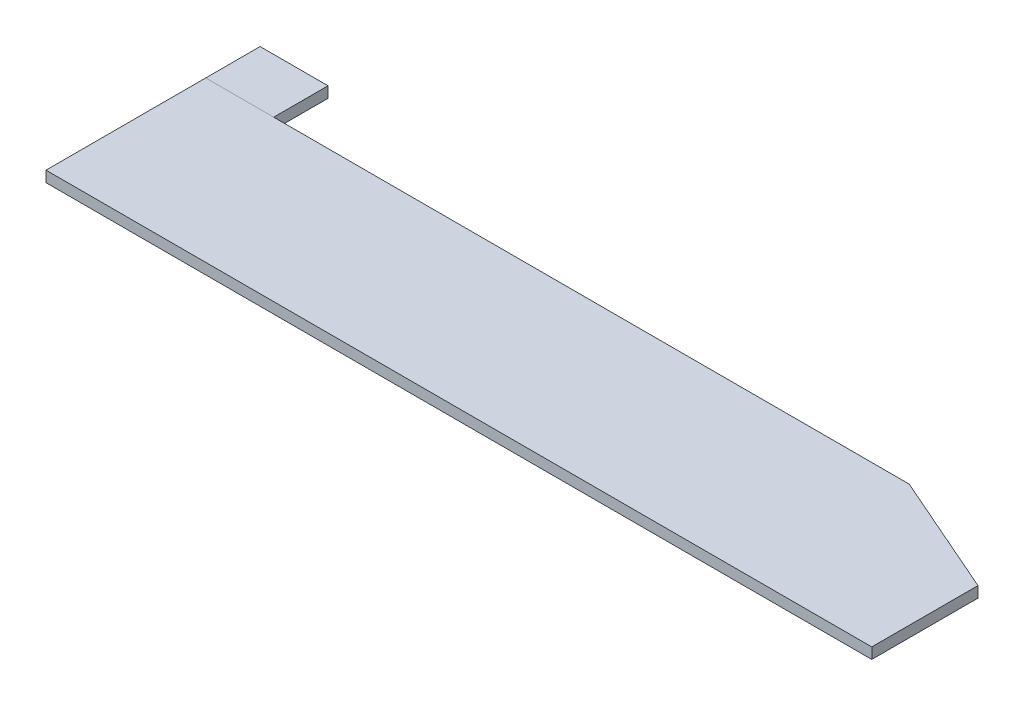
SolidWorks part; units mm, degrees
ref_plane "Front Plane" through (0, 0, 0) normal (0, 0, 1) x (1, 0, 0)
ref_plane "Top Plane" through (0, 0, 0) normal (0, 1, 0) x (1, 0, 0)
ref_plane "Right Plane" through (0, 0, 0) normal (1, 0, 0) x (0, 0, -1)
sketch "Sketch1" plane through (0, 0, 0) normal (0, 1, 0) x (1, 0, 0)
  line L0 (-43.4424, 9.168) -> (-43.4424, -14.332)
  line L1 (-43.4424, -14.332) -> (78.0576, -14.332)
  line L2 (78.0576, -14.332) -> (78.0576, 1.298)
  line L4 (60.0576, 9.168) -> (-43.4424, 9.168)
  line L5 (60.0576, 9.168) -> (78.0576, 1.298)
  dimension "D1" = 121.5
  dimension "D2" = 23.5
  dimension "D3" = 15.63
  dimension "D4" = 103.5
extrude "Boss-Extrude1" add sketch "Sketch1" along normal blind 1.6
sketch "Sketch2" plane through (0, 1.6, 0) normal (0, 1, 0) x (1, 0, 0)
  line L0 (-43.4424, -14.332) -> (78.0576, -14.332) construction
  line L1 (-43.4424, 9.168) -> (-33.4424, 9.168)
  line L2 (-43.4424, 9.168) -> (-43.4424, 17.168)
  line L3 (-43.4424, 17.168) -> (-33.4424, 17.168)
  line L4 (-33.4424, 9.168) -> (-33.4424, 17.168)
  dimension "D1" = 31.5
  dimension "D2" = 10
extrude "Boss-Extrude2" add sketch "Sketch2" against normal blind 1.6 separate body
